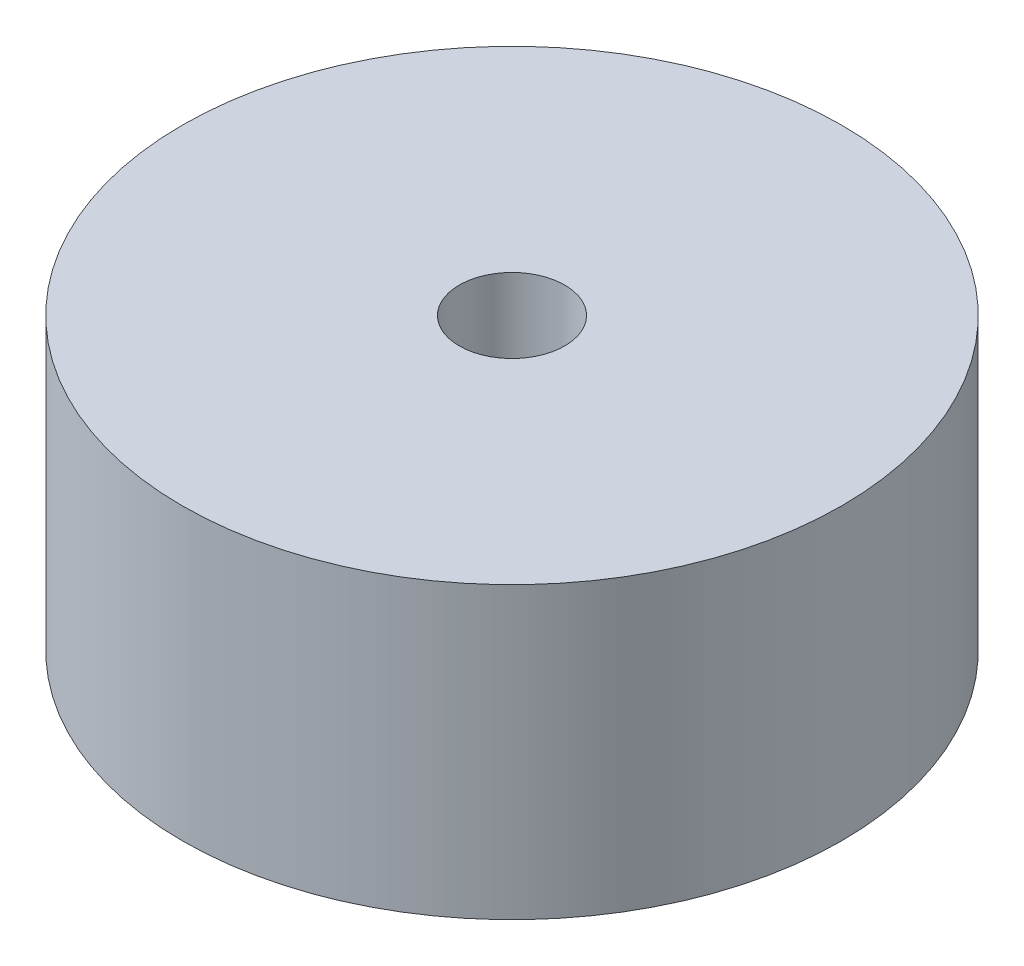
SolidWorks part; units mm, degrees
ref_plane "Front Plane" through (0, 0, 0) normal (0, 0, 1) x (1, 0, 0)
ref_plane "Top Plane" through (0, 0, 0) normal (0, 1, 0) x (1, 0, 0)
ref_plane "Right Plane" through (0, 0, 0) normal (1, 0, 0) x (0, 0, -1)
sketch "Sketch1" plane through (0, 0, 0) normal (0, 1, 0) x (1, 0, 0)
  circle A0 centre (0, 0) radius 12.5
  dimension "D1" = 25
extrude "Boss-Extrude1" add sketch "Sketch1" along normal blind 11
sketch "Sketch2" plane through (0, 11, 0) normal (0, 1, 0) x (1, 0, 0)
  circle A0 centre (0, 0) radius 2
  dimension "D1" = 4
extrude "Cut-Extrude1" cut sketch "Sketch2" against normal through all both and the other way through all
sketch "Sketch3" plane through (0, 0, 0) normal (0, -1, 0) x (1, 0, 0)
  circle A0 centre (0, 0) radius 11.5
  circle A1 centre (0, 0) radius 5
extrude "Cut-Extrude2" cut sketch "Sketch3" against normal blind 0.5
